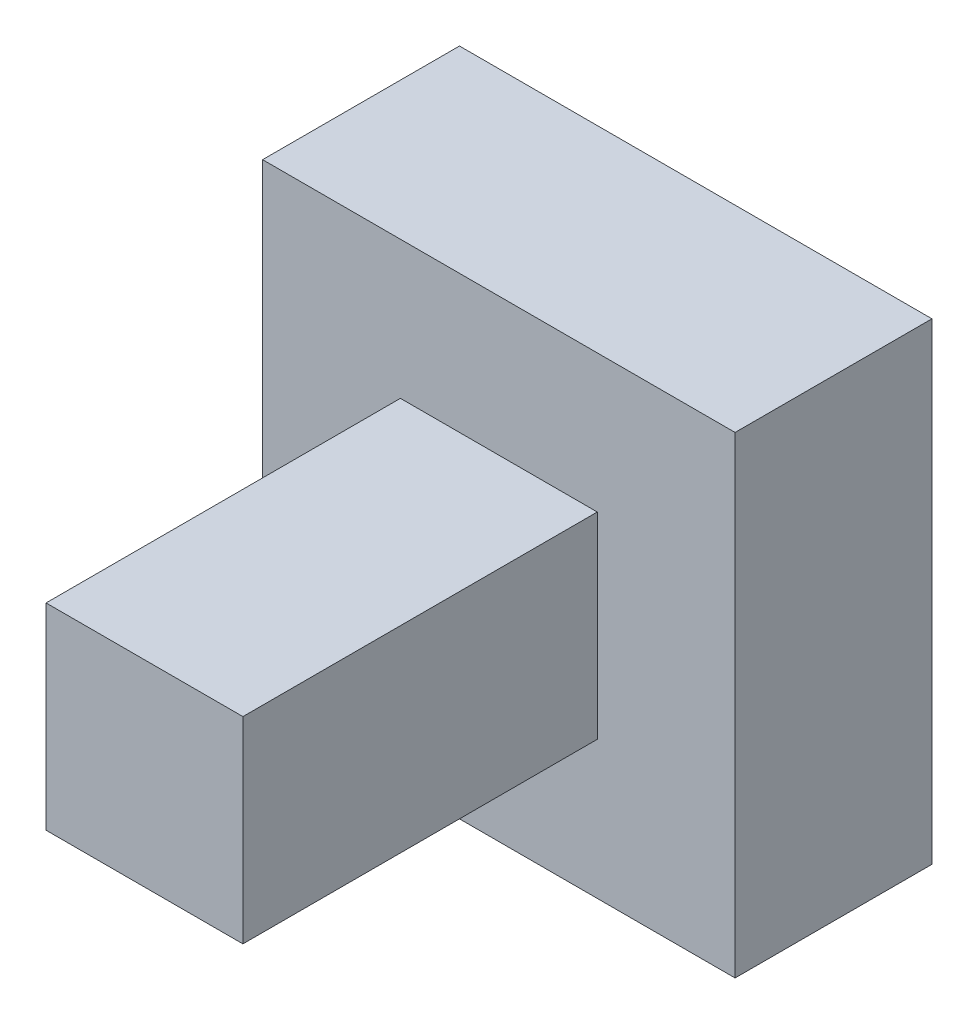
SolidWorks part; units mm, degrees
ref_plane "Płaszczyzna przednia" through (0, 0, 0) normal (0, 0, 1) x (1, 0, 0)
ref_plane "Płaszczyzna górna" through (0, 0, 0) normal (0, 1, 0) x (1, 0, 0)
ref_plane "Płaszczyzna prawa" through (0, 0, 0) normal (1, 0, 0) x (0, 0, -1)
sketch "Szkic1" plane through (0, 0, 0) normal (0, 0, 1) x (1, 0, 0)
  line L1 (-3, 3) -> (3, 3)
  line L2 (-3, 3) -> (-3, -3)
  line L3 (-3, -3) -> (3, -3)
  line L4 (3, 3) -> (3, -3)
  line L5 (-3, 3) -> (3, -3) construction
  line L6 (-3, -3) -> (3, 3) construction
  point P0 (0, 0)
  dimension "D1" = 6
extrude "Dodanie-wyciągnięcie1" add sketch "Szkic1" along normal blind 2.5
sketch "Szkic2" plane through (0, 0, 2.5) normal (0, 0, 1) x (1, 0, 0)
  line L1 (-1.25, 1.25) -> (1.25, 1.25)
  line L2 (-1.25, 1.25) -> (-1.25, -1.25)
  line L3 (-1.25, -1.25) -> (1.25, -1.25)
  line L4 (1.25, 1.25) -> (1.25, -1.25)
  line L5 (-1.25, 1.25) -> (1.25, -1.25) construction
  line L6 (-1.25, -1.25) -> (1.25, 1.25) construction
  point P0 (0, 0)
  dimension "D1" = 2.5
extrude "Dodanie-wyciągnięcie2" add sketch "Szkic2" along normal blind 4.5
